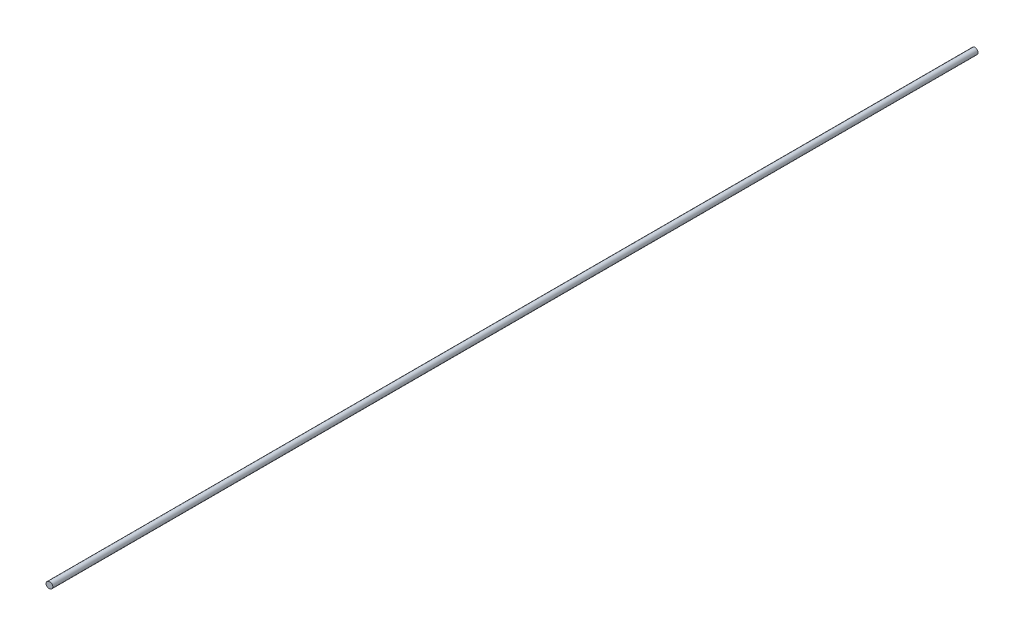
SolidWorks part; units mm, degrees
ref_plane "Front Plane" through (0, 0, 0) normal (0, 0, 1) x (1, 0, 0)
ref_plane "Top Plane" through (0, 0, 0) normal (0, 1, 0) x (1, 0, 0)
ref_plane "Right Plane" through (0, 0, 0) normal (1, 0, 0) x (0, 0, -1)
sketch "Sketch1" plane through (0, 0, 0) normal (0, 0, 1) x (1, 0, 0)
  circle A0 centre (0, 0) radius 1.5
  dimension "D1" = 3
extrude "Boss-Extrude1" add sketch "Sketch1" along normal blind 450
sketch "Sketch3" plane through (0, 0, 0) normal (0, 1, 0) x (1, 0, 0)
  line L1 (-1.5, 0) -> (-1.5, -450) construction
  line L3 (-1.5, -450) -> (1.5, -450) construction
  line L4 (-1.5, -450) -> (1.5, -450)
  line L5 (-1.5, -450) -> (1.5, -449.6762)
  line L6 (1.5, -450) -> (1.5, 0) construction
  line L7 (1.5, -449.6762) -> (1.5, -450)
  dimension "D1" = 6.16
extrude "Cut-Extrude1" cut sketch "Sketch3" against normal through all both and the other way through all
